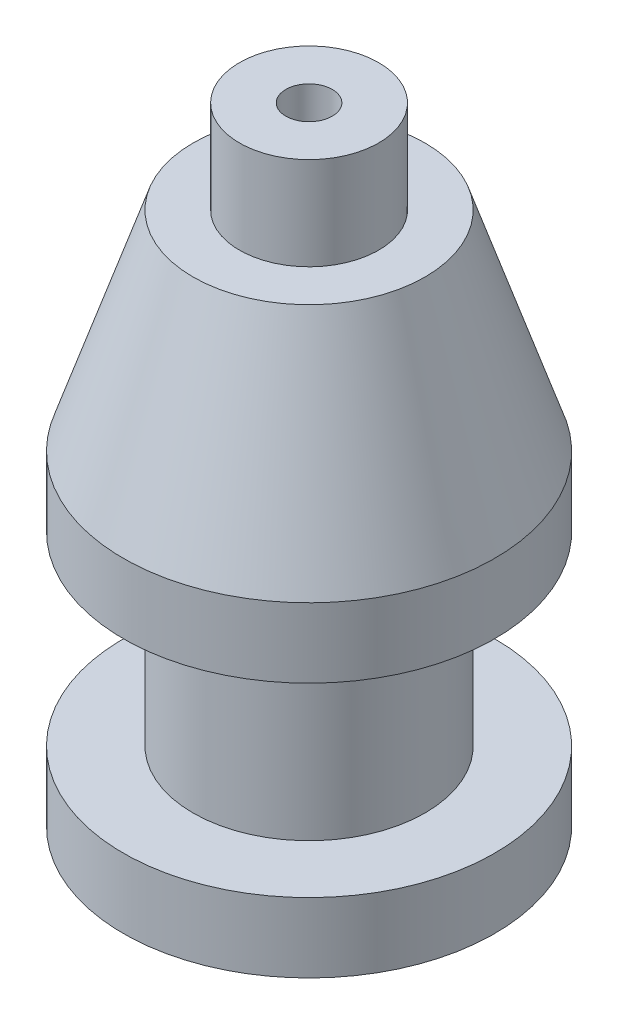
SolidWorks part; units mm, degrees
ref_plane "Front Plane" through (0, 0, 0) normal (0, 0, 1) x (1, 0, 0)
ref_plane "Top Plane" through (0, 0, 0) normal (0, 1, 0) x (1, 0, 0)
ref_plane "Right Plane" through (0, 0, 0) normal (1, 0, 0) x (0, 0, -1)
sketch "Sketch1" plane through (0, 0, 0) normal (0, 0, 1) x (1, 0, 0)
  line L0 (0, 0) -> (0, 270) construction
  line L1 (0, 0) -> (189.2637, 0) construction
  line L2 (10, 0) -> (10, 270)
  line L3 (10, 270) -> (30, 270)
  line L4 (30, 270) -> (30, 230)
  line L5 (30, 230) -> (50, 230)
  line L6 (50, 230) -> (80, 140)
  line L7 (80, 140) -> (80, 110)
  line L8 (80, 110) -> (50, 110)
  line L9 (50, 110) -> (50, 30)
  line L10 (50, 30) -> (80, 30)
  line L11 (80, 30) -> (80, 0)
  line L12 (80, 0) -> (10, 0)
  point P15 (0, 198.6027)
  point P16 (40, 230)
  point P17 (65, 30)
  point P18 (0, 0)
  point P19 (0, 270)
  dimension "D1" = 160
  dimension "D2" = 20
  dimension "D3" = 100
  dimension "D4" = 60
  dimension "D5" = 100
  dimension "D6" = 270
  dimension "D7" = 40
  dimension "D8" = 30
  dimension "D9" = 80
  dimension "D10" = 30
revolve "Revolve1" add sketch "Sketch1" angle 360 about L0
